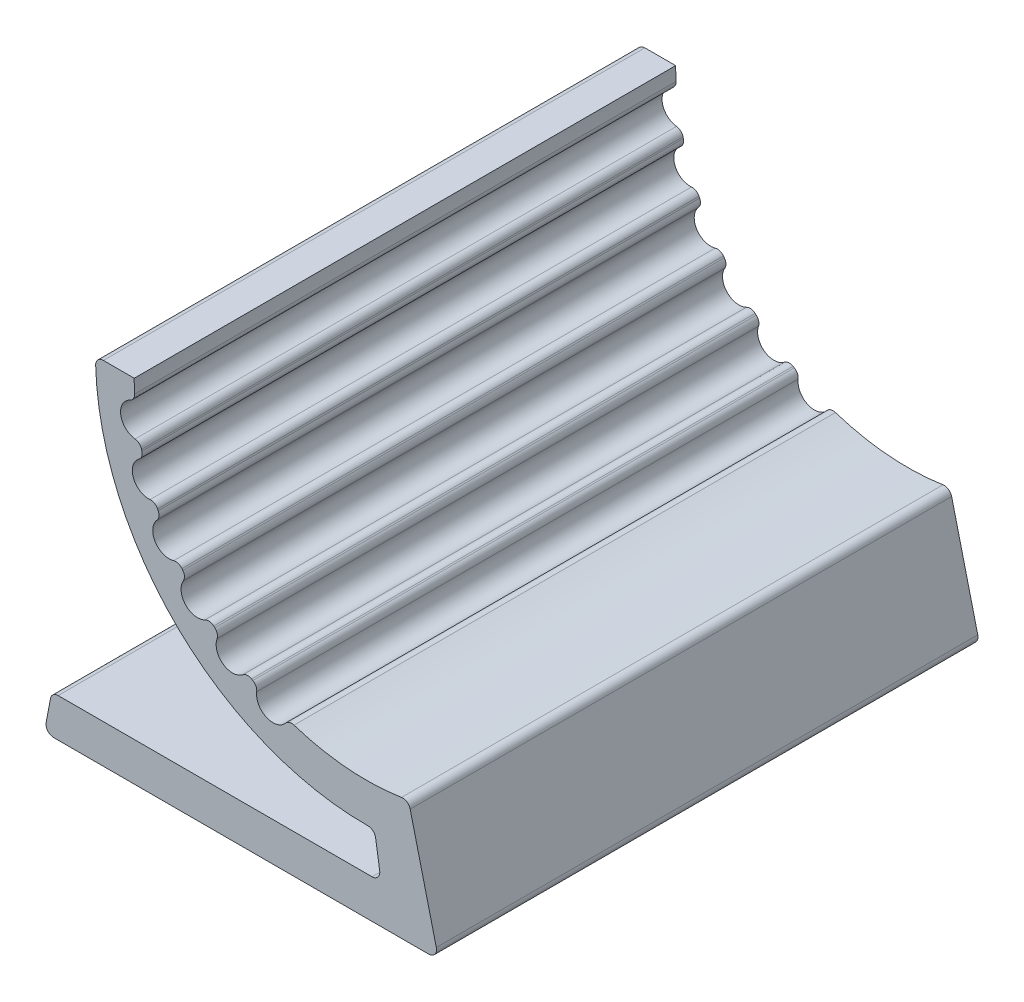
SolidWorks part; units mm, degrees
material "Pine"
ref_plane "Front Plane" through (0, 0, 0) normal (0, 0, 1) x (1, 0, 0)
ref_plane "Top Plane" through (0, 0, 0) normal (0, 1, 0) x (1, 0, 0)
ref_plane "Right Plane" through (0, 0, 0) normal (1, 0, 0) x (0, 0, -1)
sketch "Sketch1" plane through (0, 0, 0) normal (0, 0, 1) x (1, 0, 0)
  line L0 (-30, 0) -> (-35, 0)
  line L1 (6.6446, -34.3635) -> (9.3563, -45.4408)
  line L2 (5.454, -29.5001) -> (6.6446, -34.3635)
  line L3 (9.3563, -45.4408) -> (-41.6115, -45.4408)
  line L4 (1.0728, -34.9836) -> (1.9132, -40.4408)
  line L5 (-40.6646, -40.4408) -> (1.9132, -40.4408)
  line L8 (-41.6115, -45.4408) -> (-40.6646, -40.4408)
  arc A0 (-35, 0) -> (1.0728, -34.9836) centre (0, 0) ccw
  arc A1 (-30, 0) -> (-29.8929, -2.5329) centre (0, 0) ccw
  arc A2 (-29.8929, -2.5329) -> (-29.2359, -6.7276) centre (-29.6387, -4.6419) ccw
  arc A3 (-28.791, -8.4308) -> (-27.3124, -12.4109) centre (-28.1222, -10.4471) ccw
  arc A4 (-26.5375, -13.9916) -> (-24.2964, -17.5978) centre (-25.4808, -15.8344) ccw
  arc A5 (-23.2224, -18.9926) -> (-20.3086, -22.0808) centre (-21.8202, -20.5883) ccw
  arc A6 (-18.9785, -23.234) -> (-15.5084, -25.6805) centre (-17.2868, -24.5187) ccw
  arc A7 (-13.9754, -26.546) -> (-10.0878, -28.2531) centre (-12.0619, -27.4684) ccw
  arc A8 (-29.2359, -6.7276) -> (-28.791, -8.4308) centre (0, 0) ccw
  arc A9 (-27.3124, -12.4109) -> (-26.5375, -13.9916) centre (0, 0) ccw
  arc A10 (-24.2964, -17.5978) -> (-23.2224, -18.9926) centre (0, 0) ccw
  arc A11 (-20.3086, -22.0808) -> (-18.9785, -23.234) centre (0, 0) ccw
  arc A12 (-15.5084, -25.6805) -> (-13.9754, -26.546) centre (0, 0) ccw
  arc A13 (-10.0878, -28.2531) -> (5.454, -29.5001) centre (0, 0) ccw
  dimension "D1" = 70
  dimension "D2" = 60
  dimension "D9" = 4.2485
  dimension "D3" = 5
  dimension "D4" = 5
  dimension "D5" = 1.0728
  dimension "D6" = 1.9132
  dimension "D7" = 5.454
  dimension "D8" = 6.6446
  dimension "D10" = 40.6646
  dimension "D11" = 41.6115
  dimension "D12" = 6
  dimension "D13" = 6
  dimension "D14" = 6
  dimension "D15" = 6
  dimension "D16" = 6
  dimension "D17" = 12.0619
extrude "Boss-Extrude1" add sketch "Sketch1" against normal blind 70
fillet "Fillet1" radius 1 7 edges at (9.3563, -45.4408, -35) (5.454, -29.5001, -35) (1.0728, -34.9836, -35) (1.9132, -40.4408, -35) (-41.6115, -45.4408, -35) (-40.6646, -40.4408, -35) (-35, 0, -35)
fillet "Fillet2" radius 1 6 edges at (-13.9754, -26.546, -35) (-18.9785, -23.234, -35) (-23.2224, -18.9926, -35) (-26.5375, -13.9916, -35) (-28.791, -8.4308, -35) (-29.8929, -2.5329, -35)
fillet "Fillet3" radius 1 3 edges at (-20.3086, -22.0808, -35) (-15.5084, -25.6805, -35) (-10.0878, -28.2531, -35)
fillet "Fillet4" radius 1 2 edges at (-24.2964, -17.5978, -35) (-27.3124, -12.4109, -35)
fillet "Fillet5" radius 1 1 edges at (-29.2359, -6.7276, -35)
